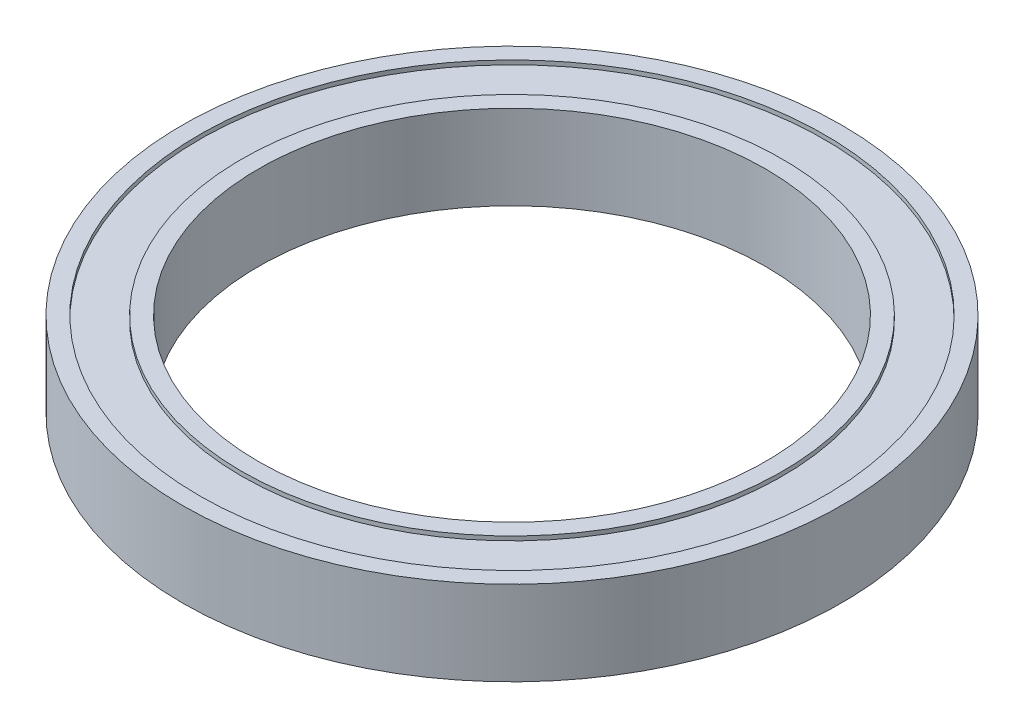
SolidWorks part; units mm, degrees
ref_plane "Front Plane" through (0, 0, 0) normal (0, 0, 1) x (1, 0, 0)
ref_plane "Top Plane" through (0, 0, 0) normal (0, 1, 0) x (1, 0, 0)
ref_plane "Right Plane" through (0, 0, 0) normal (1, 0, 0) x (0, 0, -1)
sketch "Sketch1" plane through (0, 0, 0) normal (0, 1, 0) x (1, 0, 0)
  circle A0 centre (0, 0) radius 39
  circle A1 centre (0, 0) radius 30
  dimension "D1" = 60
  dimension "D2" = 78
extrude "Boss-Extrude1" add sketch "Sketch1" along normal blind 10
sketch "Sketch2" plane through (0, 10, 0) normal (0, 1, 0) x (1, 0, 0)
  circle A0 centre (0, 0) radius 32
  circle A1 centre (0, 0) radius 37
  circle A2 centre (0, 0) radius 39 construction
  dimension "D1" = 2
  dimension "D2" = 64
extrude "Cut-Extrude1" cut sketch "Sketch2" against normal blind 0.5
sketch "Sketch3" plane through (0, 0, 0) normal (0, -1, 0) x (1, 0, 0)
  circle A0 centre (0, 0) radius 32
  circle A2 centre (0, 0) radius 37
extrude "Cut-Extrude2" cut sketch "Sketch3" against normal blind 0.5
